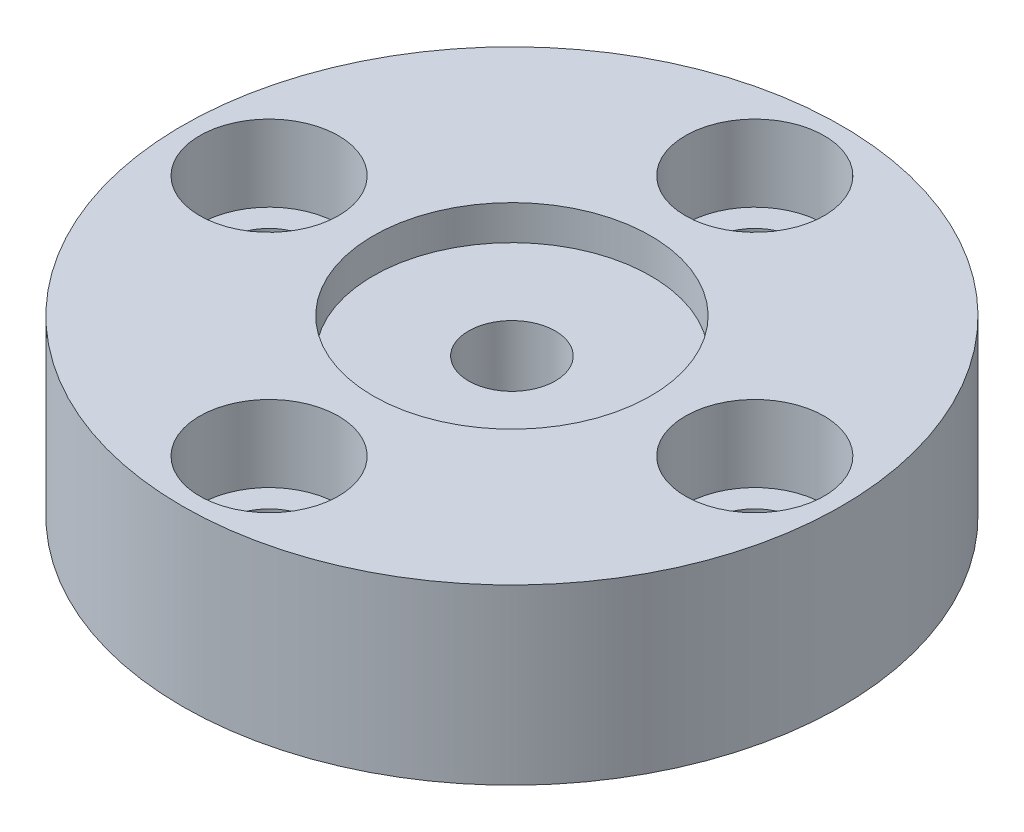
SolidWorks part; units mm, degrees
ref_plane "前视基准面" through (0, 0, 0) normal (0, 0, 1) x (1, 0, 0)
ref_plane "上视基准面" through (0, 0, 0) normal (0, 1, 0) x (1, 0, 0)
ref_plane "右视基准面" through (0, 0, 0) normal (1, 0, 0) x (0, 0, -1)
other "Configuration Table"
sketch "草图1" plane through (0, 0, 0) normal (0, 1, 0) x (1, 0, 0)
  circle A0 centre (0, 0) radius 19
  dimension "D1" = 38
extrude "凸台-拉伸1" add sketch "草图1" along normal blind 10
sketch "草图2" plane through (0, 10, 0) normal (0, 1, 0) x (1, 0, 0)
  circle A0 centre (0, 0) radius 8
  dimension "D1" = 16
extrude "切除-拉伸1" cut sketch "草图2" against normal blind 2
sketch "草图3" plane through (0, 0, 0) normal (0, -1, 0) x (1, 0, 0)
  circle A0 centre (0, 0) radius 6
  dimension "D1" = 12
extrude "切除-拉伸2" cut sketch "草图3" against normal blind 3
sketch "草图4" plane through (0, 3, 0) normal (0, -1, 0) x (1, 0, 0)
  circle A0 centre (0, 0) radius 2.5
  dimension "D1" = 5
extrude "切除-拉伸3" cut sketch "草图4" against normal blind 16
sketch "草图5" plane through (0, 10, 0) normal (0, 1, 0) x (1, 0, 0)
  circle A0 centre (0, 14) radius 4
  point P2 (0, 0)
  point P4 (0, 0)
  dimension "D1" = 8
  dimension "D2" = 14
extrude "切除-拉伸4" cut sketch "草图5" against normal blind 4.4 contours A0
sketch "草图6" plane through (0, 5.6, 0) normal (0, 1, 0) x (1, 0, 0)
  circle A0 centre (0, 14) radius 2.5
  dimension "D1" = 5
extrude "切除-拉伸5" cut sketch "草图6" against normal through all
cosmetic thread "装饰螺纹线1" parameters "D2"=6
pattern_circular "阵列(圆周)1" count 4 over 360 about axis through (0, 0, 0) along (0, 1, 0) of "切除-拉伸4", "切除-拉伸5"
